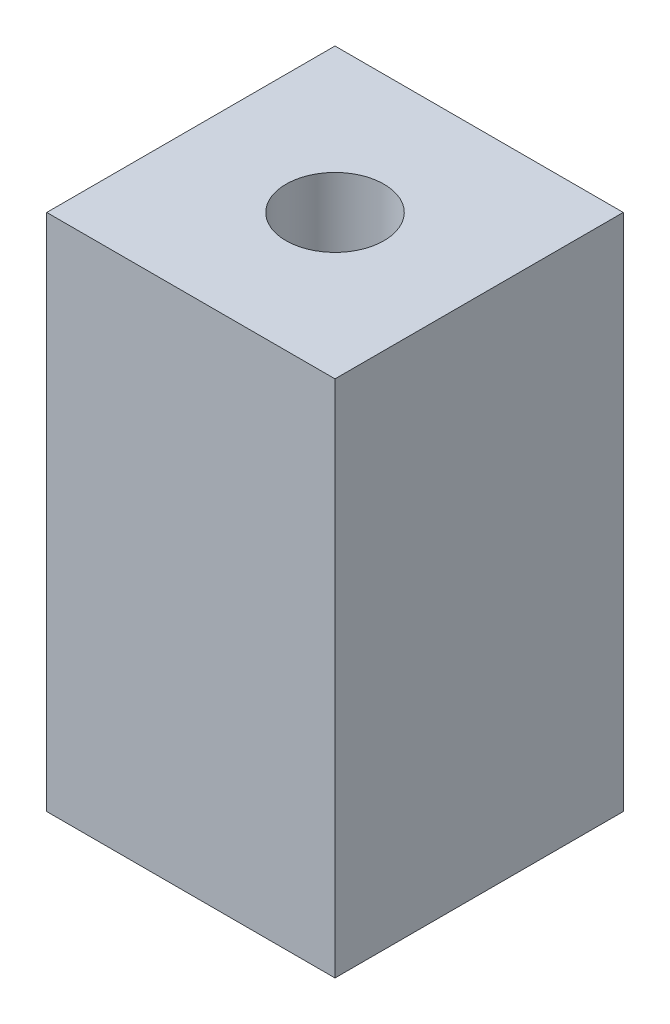
SolidWorks part; units mm, degrees
ref_plane "Front Plane" through (0, 0, 0) normal (0, 0, 1) x (1, 0, 0)
ref_plane "Top Plane" through (0, 0, 0) normal (0, 1, 0) x (1, 0, 0)
ref_plane "Right Plane" through (0, 0, 0) normal (1, 0, 0) x (0, 0, -1)
sketch "Sketch2" plane through (0, 0, 0) normal (0, 1, 0) x (1, 0, 0)
  line L1 (-7.5, 7.5) -> (7.5, 7.5)
  line L2 (-7.5, 7.5) -> (-7.5, -7.5)
  line L3 (-7.5, -7.5) -> (7.5, -7.5)
  line L4 (7.5, 7.5) -> (7.5, -7.5)
  circle A0 centre (0, 0) radius 2.55
  dimension "D1" = 15
  dimension "D2" = 15
  dimension "D3" = 7.5
  dimension "D4" = 7.5
extrude "Boss-Extrude1" add sketch "Sketch2" along normal blind 27
